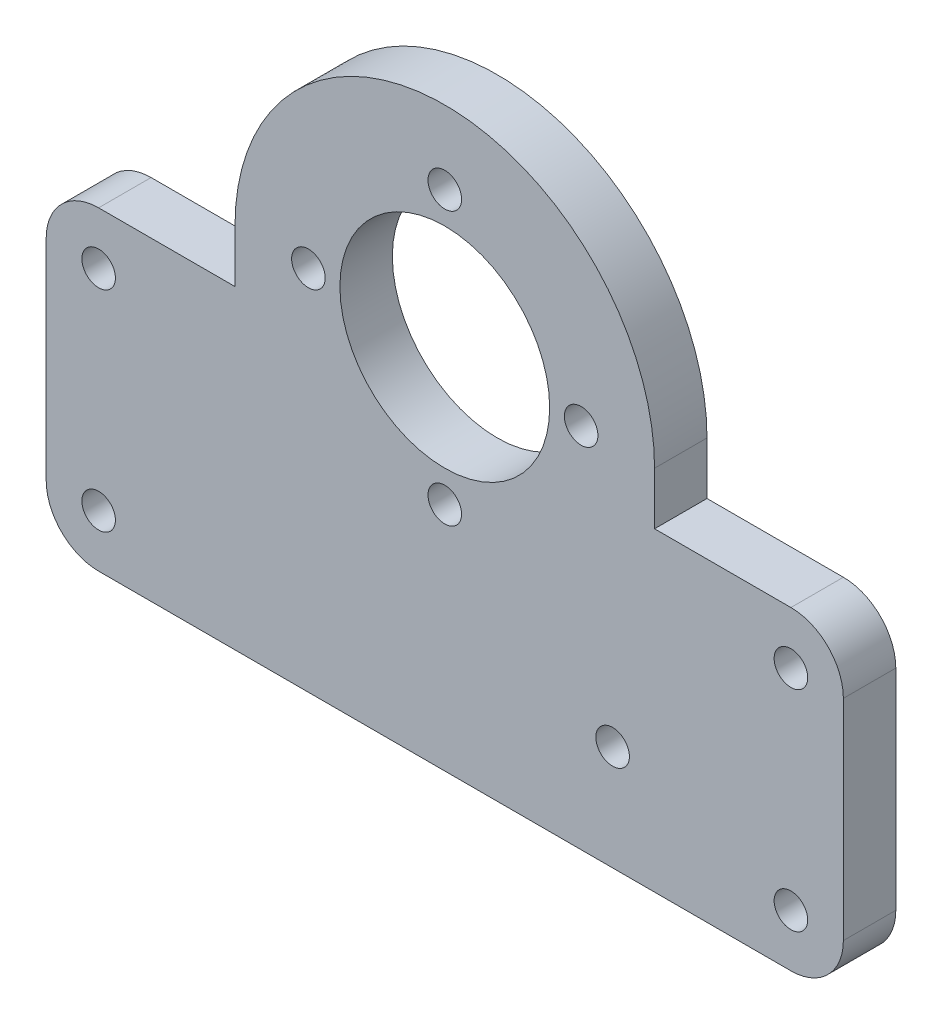
SolidWorks part; units mm, degrees
material "MC901"
ref_plane "Front" through (0, 0, 0) normal (0, 0, 1) x (1, 0, 0)
ref_plane "Top" through (0, 0, 0) normal (0, 1, 0) x (1, 0, 0)
ref_plane "Right" through (0, 0, 0) normal (1, 0, 0) x (0, 0, -1)
sketch "ｽｹｯﾁ1" plane through (0, 0, 0) normal (0, 0, 1) x (1, 0, 0)
  line L1 (-38, -30) -> (38, -30)
  line L2 (-38, -30) -> (-38, 30)
  line L3 (-38, 30) -> (38, 30)
  line L4 (38, -30) -> (38, 30)
  line L5 (-38, -30) -> (38, 30) construction
  line L6 (-38, 30) -> (38, -30) construction
  point P0 (0, 0)
  dimension "D1" = 76
  dimension "D2" = 60
extrude "ﾎﾞｽ - 押し出し1" add sketch "ｽｹｯﾁ1" along normal blind 5
fillet "ﾌｨﾚｯﾄ1" radius 5 4 edges at (-38, -30, 2.5) (38, -30, 2.5) (38, 30, 2.5) (-38, 30, 2.5)
sketch "ｽｹｯﾁ4" plane through (0, 0, 0) normal (0, 0, -1) x (-1, 0, 0)
  line L0 (-33, 30) -> (-33, -30) construction
  line L1 (-33, 30) -> (33, 30) construction
  line L2 (33, 20) -> (33, -30) construction
  line L3 (33, -30) -> (-33, -30) construction
  line L5 (38, 25) -> (38, -25) construction
  circle A2 centre (-33, -5) radius 1.6
  circle A3 centre (-33, -25) radius 1.6
  circle A4 centre (33, -5) radius 1.6
  circle A5 centre (33, -25) radius 1.6
  dimension "D3" = 3.2
  dimension "D5" = 35
  dimension "D1" = 35
  dimension "D4" = 5
  dimension "D6" = 5
  dimension "D2" = 5
extrude "ｶｯﾄ - 押し出し3" cut sketch "ｽｹｯﾁ4" against normal blind 5
sketch "ｽｹｯﾁ11" plane through (0, 0, 0) normal (0, 0, -1) x (-1, 0, 0)
  line L0 (0, 30) -> (0, -30) construction
  line L1 (-33, 30) -> (33, 30) construction
  line L2 (33, -30) -> (-33, -30) construction
  circle A0 centre (0, 5) radius 10
  circle A1 centre (0, 18) radius 1.6
  circle A5 centre (13, 5) radius 1.6
  circle A6 centre (0, -8) radius 1.6
  circle A7 centre (-13, 5) radius 1.6
  dimension "D1" = 20
  dimension "D2" = 25
  dimension "D3" = 13
  dimension "D5" = 3.2
  dimension "D4" = 4
extrude "ｶｯﾄ - 押し出し11" cut sketch "ｽｹｯﾁ11" against normal blind 10
sketch "ｽｹｯﾁ12" plane through (0, 0, 0) normal (0, 0, -1) x (-1, 0, 0)
  line L0 (-38, 0) -> (-20, 0)
  line L1 (-38, -25) -> (-38, 25) construction
  line L2 (-20, 5) -> (-20, 0)
  line L3 (20, 5) -> (20, 0)
  line L4 (20, 0) -> (38, 0)
  line L5 (38, 25) -> (38, -25) construction
  line L6 (38, 0) -> (38, 30)
  line L7 (38, 30) -> (-38, 30)
  line L8 (-38, 30) -> (-38, 0)
  arc A0 (-20, 5) -> (20, 5) centre (0, 5) cw
  dimension "D1" = 20
extrude "ｶｯﾄ - 押し出し12" cut sketch "ｽｹｯﾁ12" against normal blind 13.5
fillet "ﾌｨﾚｯﾄ2" radius 5 2 edges at (-38, 0, 2.5) (38, 0, 2.5)
sketch "ｽｹｯﾁ13" plane through (0, 0, 5) normal (0, 0, 1) x (1, 0, 0)
  line L0 (38, -25) -> (38, -5) construction
  line L1 (-33, -30) -> (33, -30) construction
  circle A0 centre (16, -20) radius 1.6
  dimension "D1" = 3.2
  dimension "D2" = 22
  dimension "D3" = 10
extrude "ｶｯﾄ - 押し出し13" cut sketch "ｽｹｯﾁ13" against normal through all
